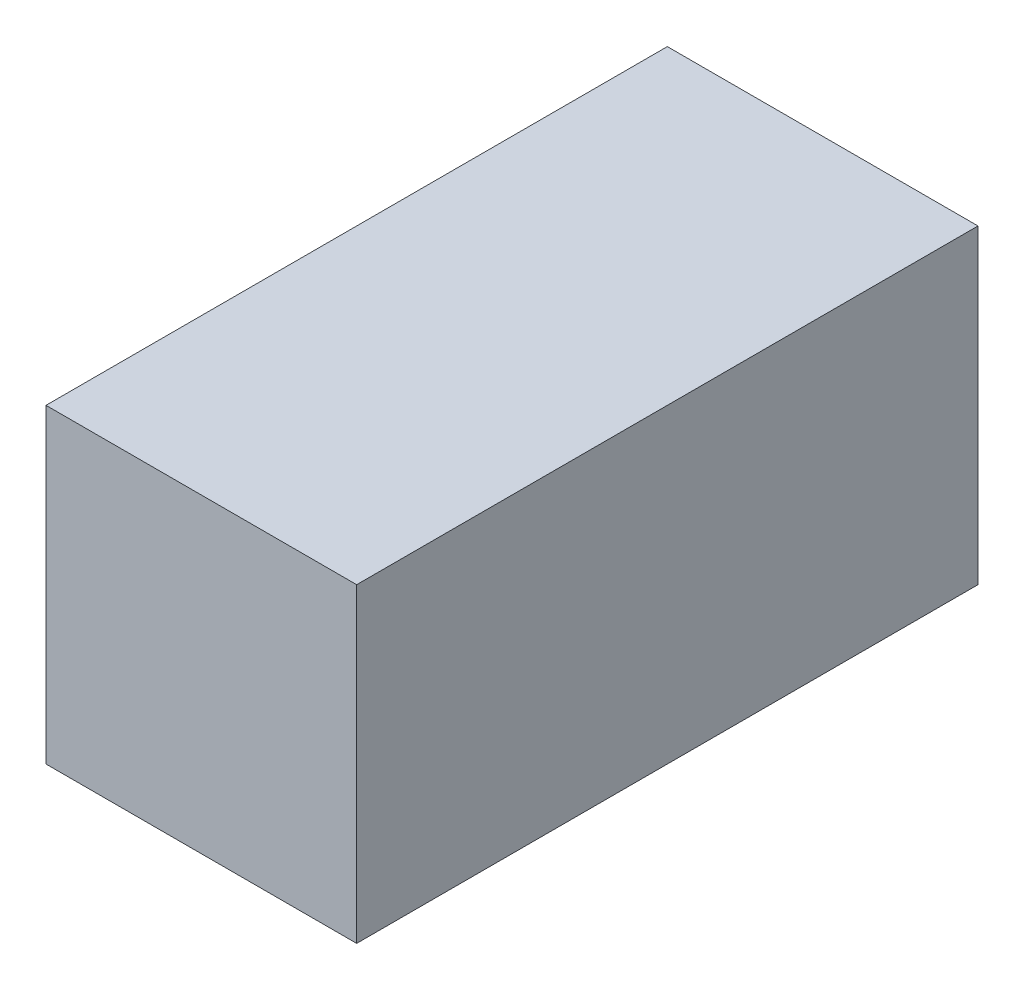
SolidWorks part; units mm, degrees
ref_plane "Front Plane" through (0, 0, 0) normal (0, 0, 1) x (1, 0, 0)
ref_plane "Top Plane" through (0, 0, 0) normal (0, 1, 0) x (1, 0, 0)
ref_plane "Right Plane" through (0, 0, 0) normal (1, 0, 0) x (0, 0, -1)
sketch "Sketch1" plane through (0, 0, 0) normal (0, 1, 0) x (1, 0, 0)
  line L1 (-5, -10) -> (5, -10)
  line L2 (-5, -10) -> (-5, 10)
  line L3 (-5, 10) -> (5, 10)
  line L4 (5, -10) -> (5, 10)
  line L5 (-5, -10) -> (5, 10) construction
  line L6 (-5, 10) -> (5, -10) construction
  point P0 (0, 0)
  dimension "D1" = 20
  dimension "D2" = 10
extrude "Boss-Extrude1" add sketch "Sketch1" along normal mid plane 10
